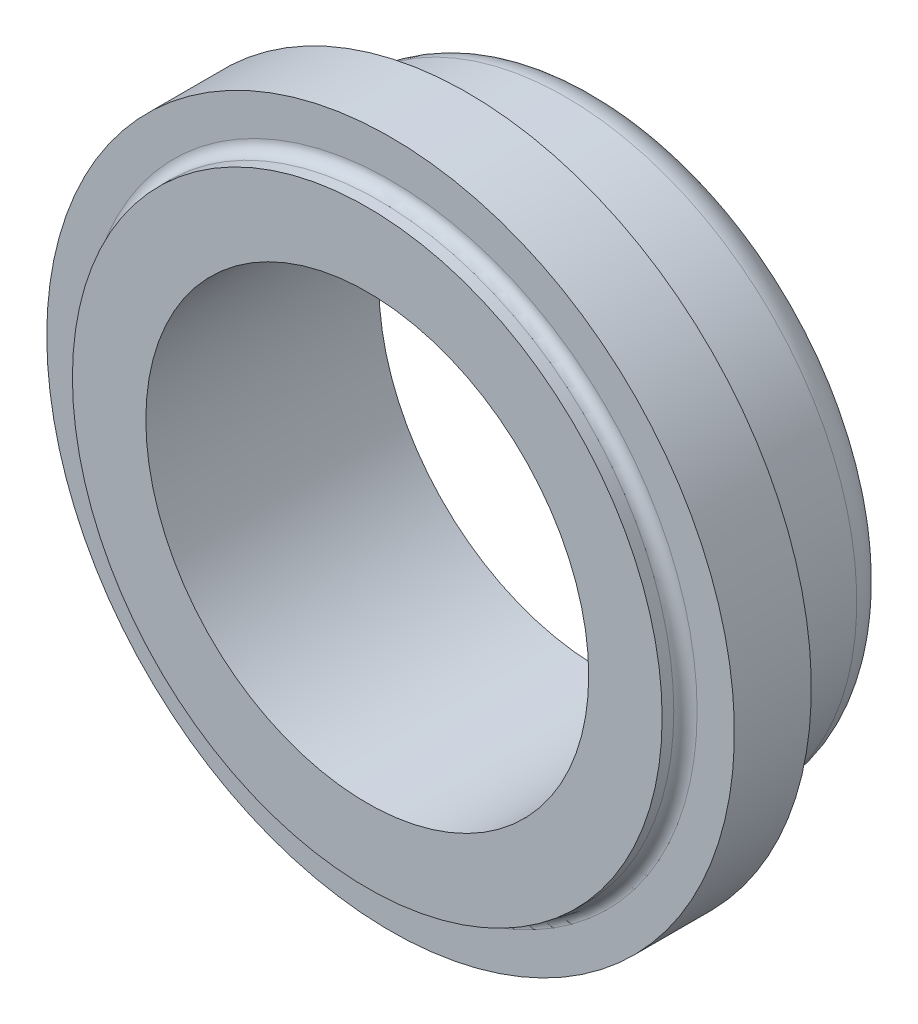
SolidWorks part; units mm, degrees
ref_plane "Front Plane" through (0, 0, 0) normal (0, 0, 1) x (1, 0, 0)
ref_plane "Top Plane" through (0, 0, 0) normal (0, 1, 0) x (1, 0, 0)
ref_plane "Right Plane" through (0, 0, 0) normal (1, 0, 0) x (0, 0, -1)
sketch "Sketch1" plane through (0, 0, 0) normal (0, 1, 0) x (1, 0, 0)
  line L0 (0, 30.3635) -> (0, -32.0176) construction
sketch "Sketch2" plane through (0, 0, 0) normal (0, 1, 0) x (1, 0, 0)
  line L5 (-23, 2) -> (-23, 3.5)
  line L7 (-25, 5.5) -> (-25, 18)
  line L10 (-25, 18) -> (-19, 18)
  line L14 (-27.5, 2) -> (-23, 2)
  line L19 (-27.5, 2) -> (-27.5, 6.6)
  line L20 (-27.5, 6.6) -> (-29.5, 6.6)
  line L21 (-29.5, 6.6) -> (-29.5, 0)
  line L23 (-19, 18) -> (-19, -2)
  line L24 (-25, 5.5) -> (-23, 3.5)
  line L28 (-29.5, 0) -> (-25.3, 0)
  line L29 (-29.9, 0) -> (29.9, 0) construction
  line L30 (-25.3, 0) -> (-25.3, -2)
  line L31 (0, 200013.4407) -> (0, -200007.4209) construction
  line L32 (-34.825, -2) -> (34.825, -2) construction
  line L33 (-25.3, -2) -> (-19, -2)
  dimension "D2" = 19
  dimension "D3" = 20
  dimension "D4" = 6.3
  dimension "D5" = 6
  dimension "D6" = 1.5
  dimension "D7" = 3.5
  dimension "D8" = 4
  dimension "D9" = 2
  dimension "D10" = 6.6
  dimension "D11" = 29.5
  dimension "D12" = 2
  dimension "D14" = 2
  dimension "D15" = 4.5
revolve "Revolve1" add sketch "Sketch2" angle 360 about L0
fillet "Fillet1" radius 3 1 edges at (-25, 0, -18)
fillet "Fillet2" radius 1 1 edges at (-25.3, 0, 0)
ref_plane "Plane1" through (0, 0, -12) normal (0, 0, 1) x (1, 0, 0)
ref_point "Point1"
ref_point "Point2"
ref_plane "Plane2" through (0, 0, 0) normal (-0.6045, -0.7966, 0) x (-0.7966, 0.6045, 0)
hole_wizard "CBORE for M2.5 SHCS1" positions "3DSketch3" profile "Sketch4" counterbore size "M2.5" standard "ANSI Metric"
sketch3d "3DSketch3"
  point P0 (-19.9151, 15.1125, -12)
  point P2 (19.9151, -15.1125, -12)
  point P8 (0, 0, 0)
  point P9 (0, 0, 0)
  point P10 (0, 0, 0)
  point P11 (0, 0, 0)
sketch "Sketch4" plane through (-19.9151, 15.1125, -12) normal (0, 0, 1) x (-0.6045, -0.7966, 0)
  line L0 (0, 0) -> (0, 8.8712)
  line L1 (0, 8.8712) -> (1.45, 8)
  line L2 (1.45, 8) -> (1.45, 4.5)
  line L3 (1.45, 4.5) -> (2.75, 4.5)
  line L4 (2.75, 4.5) -> (2.75, 0)
  line L5 (2.75, 0) -> (0, 0)
  line L10 (0, 8.8712) -> (-1.45, 8) construction
  line L11 (0, -6.35) -> (0, 107.95) construction
  dimension "Hole Dia." = 2.9
  dimension "Hole Depth" = 8
  dimension "C'Bore Dia." = 5.5
  dimension "C'Bore Depth" = 4.5
  dimension "Drill Angle" = 118
